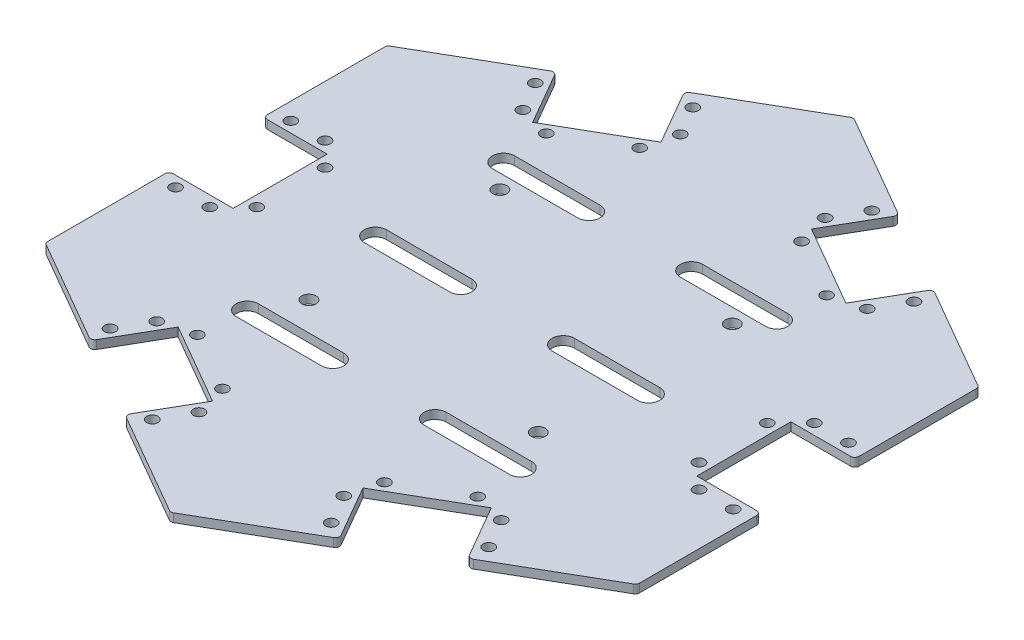
SolidWorks part; units mm, degrees
ref_plane "Front Plane" through (0, 0, 0) normal (0, 0, 1) x (1, 0, 0)
ref_plane "Top Plane" through (0, 0, 0) normal (0, 1, 0) x (1, 0, 0)
ref_plane "Right Plane" through (0, 0, 0) normal (1, 0, 0) x (0, 0, -1)
sketch "Sketch1" plane through (0, 0, 0) normal (0, 1, 0) x (1, 0, 0)
  line L0 (-69.282, 0) -> (69.282, 0) construction
  line L1 (0, -80) -> (69.282, -40)
  line L2 (69.282, -40) -> (69.282, 40)
  line L3 (69.282, 40) -> (0, 80)
  line L4 (0, 80) -> (-69.282, 40)
  line L5 (-69.282, 40) -> (-69.282, -40)
  line L6 (-69.282, -40) -> (0, -80)
  line L7 (-69.282, 40) -> (69.282, -40) construction
  line L8 (0, 80) -> (0, -80) construction
  line L9 (0, 80) -> (69.282, 40)
  line L10 (-69.282, 40) -> (0, 80)
  line L11 (-69.282, -40) -> (-69.282, 40)
  line L12 (0, -80) -> (-69.282, -40)
  line L13 (69.282, -40) -> (0, -80)
  line L14 (69.282, 40) -> (69.282, -40)
  line L15 (-69.282, -40) -> (69.282, 40) construction
  circle A0 centre (0, 0) radius 69.282 construction
  circle A1 centre (65.282, 13.5) radius 1.3
  circle A2 centre (57.282, 13.5) radius 1.3
  circle A3 centre (51.782, 8) radius 1.3
  circle A4 centre (51.782, -8) radius 1.3
  circle A5 centre (57.282, -13.5) radius 1.3
  circle A6 centre (65.282, -13.5) radius 1.3
  circle A7 centre (32.8192, -40.8446) radius 1.3
  circle A8 centre (20.9497, -63.2859) radius 1.3
  circle A9 centre (16.9497, -56.3577) radius 1.3
  circle A10 centre (18.9628, -48.8446) radius 1.3
  circle A11 centre (44.3324, -49.7859) radius 1.3
  circle A12 centre (40.3324, -42.8577) radius 1.3
  circle A13 centre (-44.3324, -49.7859) radius 1.3
  circle A14 centre (-40.3324, -42.8577) radius 1.3
  circle A15 centre (-32.8192, -40.8446) radius 1.3
  circle A16 centre (-18.9628, -48.8446) radius 1.3
  circle A17 centre (-16.9497, -56.3577) radius 1.3
  circle A18 centre (-20.9497, -63.2859) radius 1.3
  circle A19 centre (18.9628, 48.8446) radius 1.3
  circle A20 centre (44.3324, 49.7859) radius 1.3
  circle A21 centre (40.3324, 42.8577) radius 1.3
  circle A22 centre (32.8192, 40.8446) radius 1.3
  circle A23 centre (20.9497, 63.2859) radius 1.3
  circle A24 centre (16.9497, 56.3577) radius 1.3
  circle A25 centre (-65.282, 13.5) radius 1.3
  circle A26 centre (-20.9497, 63.2859) radius 1.3
  circle A27 centre (-16.9497, 56.3577) radius 1.3
  circle A28 centre (-18.9628, 48.8446) radius 1.3
  circle A29 centre (-32.8192, 40.8446) radius 1.3
  circle A30 centre (-44.3324, 49.7859) radius 1.3
  circle A31 centre (-40.3324, 42.8577) radius 1.3
  circle A32 centre (-57.282, 13.5) radius 1.3
  circle A33 centre (-51.782, 8) radius 1.3
  circle A34 centre (-51.782, -8) radius 1.3
  circle A35 centre (-57.282, -13.5) radius 1.3
  circle A36 centre (-65.282, -13.5) radius 1.3
  dimension "D6" = 2.6
  dimension "D1" = 4
  dimension "D2" = 8
  dimension "D3" = 5.5
  dimension "D4" = 5.5
  dimension "D5" = 8
  dimension "D7" = 80
extrude "Boss-Extrude1" add sketch "Sketch1" along normal blind 2 contours L5 L6 L1 L2 L3 L4 A36 A35 A34 A32 A31 A30 A29 A27 A25 A24 A23 A21 A15 A13 A12 A11 A9 A6 A4 A3 A2 A1
sketch "Sketch2" plane through (0, 2, 0) normal (0, 1, 0) x (1, 0, 0)
  line L0 (-69.282, 40) -> (69.282, -40) construction
  line L1 (0, 80) -> (0, -80) construction
  line L2 (-69.282, -40) -> (69.282, 40) construction
  line L3 (69.282, -40) -> (69.282, 40) construction
  line L4 (69.282, 11) -> (54.282, 11)
  line L5 (69.282, 11) -> (69.282, -11)
  line L6 (69.282, -11) -> (54.282, -11)
  line L7 (54.282, 11) -> (54.282, -11)
  line L8 (-69.282, 0) -> (69.282, 0) construction
  line L9 (-69.282, 40) -> (-69.282, -40) construction
  line L10 (44.1673, -54.5) -> (36.6673, -41.5096)
  line L11 (17.6147, -52.5096) -> (36.6673, -41.5096)
  line L12 (25.1147, -65.5) -> (17.6147, -52.5096)
  line L13 (25.1147, -65.5) -> (44.1673, -54.5)
  line L14 (-25.1147, -65.5) -> (-44.1673, -54.5)
  line L15 (-25.1147, -65.5) -> (-17.6147, -52.5096)
  line L16 (-17.6147, -52.5096) -> (-36.6673, -41.5096)
  line L17 (-44.1673, -54.5) -> (-36.6673, -41.5096)
  line L18 (25.1147, 65.5) -> (17.6147, 52.5096)
  line L19 (36.6673, 41.5096) -> (17.6147, 52.5096)
  line L20 (44.1673, 54.5) -> (36.6673, 41.5096)
  line L21 (44.1673, 54.5) -> (25.1147, 65.5)
  line L22 (-44.1673, 54.5) -> (-25.1147, 65.5)
  line L23 (-44.1673, 54.5) -> (-36.6673, 41.5096)
  line L24 (-36.6673, 41.5096) -> (-17.6147, 52.5096)
  line L25 (-25.1147, 65.5) -> (-17.6147, 52.5096)
  line L26 (-69.282, 11) -> (-54.282, 11)
  line L27 (-54.282, 11) -> (-54.282, -11)
  line L28 (-69.282, -11) -> (-54.282, -11)
  line L29 (-69.282, 11) -> (-69.282, -11)
  dimension "D1" = 22
  dimension "D2" = 15
extrude "Cut-Extrude1" cut sketch "Sketch2" against normal up to surface (2 mm away) up to face at (-65.282, 0, 14.8)
fillet "Fillet1" radius 1 18 edges at (-44.1673, 1, -54.5) (-25.1147, 1, -65.5) (-69.282, 1, -40) (-69.282, 1, -11) (-69.282, 1, 11) (-69.282, 1, 40) (-44.1673, 1, 54.5) (-25.1147, 1, 65.5) (0, 1, 80) (25.1147, 1, 65.5) (44.1673, 1, 54.5) (69.282, 1, 40) (69.282, 1, 11) (69.282, 1, -11) (69.282, 1, -40) (44.1673, 1, -54.5) (25.1147, 1, -65.5) (0, 1, -80)
sketch "Sketch3" plane through (0, 2, 0) normal (0, 1, 0) x (1, 0, 0)
  line L0 (-32, 32.6) -> (-12, 32.6)
  line L1 (-32, 2.6) -> (-12, 2.6)
  line L3 (-32, -2.6) -> (-12, -2.6)
  line L4 (-32, 27.4) -> (-12, 27.4)
  line L5 (-32, -27.4) -> (-12, -27.4)
  line L6 (-32, -32.6) -> (-12, -32.6)
  line L7 (0, 79.8453) -> (0, -79.8453) construction
  line L8 (32, -32.6) -> (12, -32.6)
  line L9 (32, -27.4) -> (12, -27.4)
  line L10 (32, 27.4) -> (12, 27.4)
  line L11 (32, -2.6) -> (12, -2.6)
  line L12 (32, 2.6) -> (12, 2.6)
  line L13 (32, 32.6) -> (12, 32.6)
  arc A0 (-32, 2.6) -> (-32, -2.6) centre (-32, 0) ccw
  arc A1 (-12, -2.6) -> (-12, 2.6) centre (-12, 0) ccw
  arc A2 (-32, 32.6) -> (-32, 27.4) centre (-32, 30) ccw
  arc A3 (-12, 27.4) -> (-12, 32.6) centre (-12, 30) ccw
  arc A4 (-32, -27.4) -> (-32, -32.6) centre (-32, -30) ccw
  arc A5 (-12, -32.6) -> (-12, -27.4) centre (-12, -30) ccw
  arc A6 (0.5, 79.7113) -> (-0.5, 79.7113) centre (0, 78.8453) ccw construction
  arc A7 (-0.5, -79.7113) -> (0.5, -79.7113) centre (0, -78.8453) ccw construction
  arc A8 (12, -32.6) -> (12, -27.4) centre (12, -30) cw
  arc A9 (32, -27.4) -> (32, -32.6) centre (32, -30) cw
  arc A10 (12, 27.4) -> (12, 32.6) centre (12, 30) cw
  arc A11 (32, 32.6) -> (32, 27.4) centre (32, 30) cw
  arc A12 (12, -2.6) -> (12, 2.6) centre (12, 0) cw
  arc A13 (32, 2.6) -> (32, -2.6) centre (32, 0) cw
  dimension "D1" = 2.6
  dimension "D2" = 20
  dimension "D3" = 12
  dimension "D6" = 30
  dimension "D7" = 30
  dimension "D4" = 2
  dimension "D5" = 2
extrude "Cut-Extrude2" cut sketch "Sketch3" against normal up to surface (2 mm away) up to face at (0, 0, 0)
sketch "Sketch5" plane through (0, 2, 0) normal (0, 1, 0) x (1, 0, 0)
  line L1 (-26.85, 24) -> (27.5843, 24) construction
  line L2 (-26.85, 24) -> (-26.85, -20.7) construction
  line L3 (-26.85, -20.7) -> (26.85, -20.7) construction
  line L7 (-28.5, 25.65) -> (28.5, 25.65) construction
  line L8 (-28.5, 25.65) -> (-28.5, -22.35) construction
  line L9 (-28.5, -22.35) -> (28.5, -22.35) construction
  line L10 (28.5, 25.65) -> (28.5, -22.35) construction
  circle A0 centre (-26.85, 24) radius 1.65
  circle A1 centre (27.5843, 24) radius 1.65
  circle A2 centre (26.85, -20.7) radius 1.65
  circle A3 centre (-26.85, -20.7) radius 1.65
  point P0 (0, 0)
  point P6 (0, 0)
  dimension "D3" = 3.3
  dimension "D1" = 57
  dimension "D2" = 48
  dimension "D4" = 1.65
  dimension "D5" = 1.65
  dimension "D6" = 24
  dimension "D7" = 1.65
  dimension "D8" = 28.5
extrude "Cut-Extrude3" cut sketch "Sketch5" against normal up to surface (2 mm away) up to face at (-22, 0, -30)
equation "\"D7@Sketch3\"=\"D6@Sketch3\""
